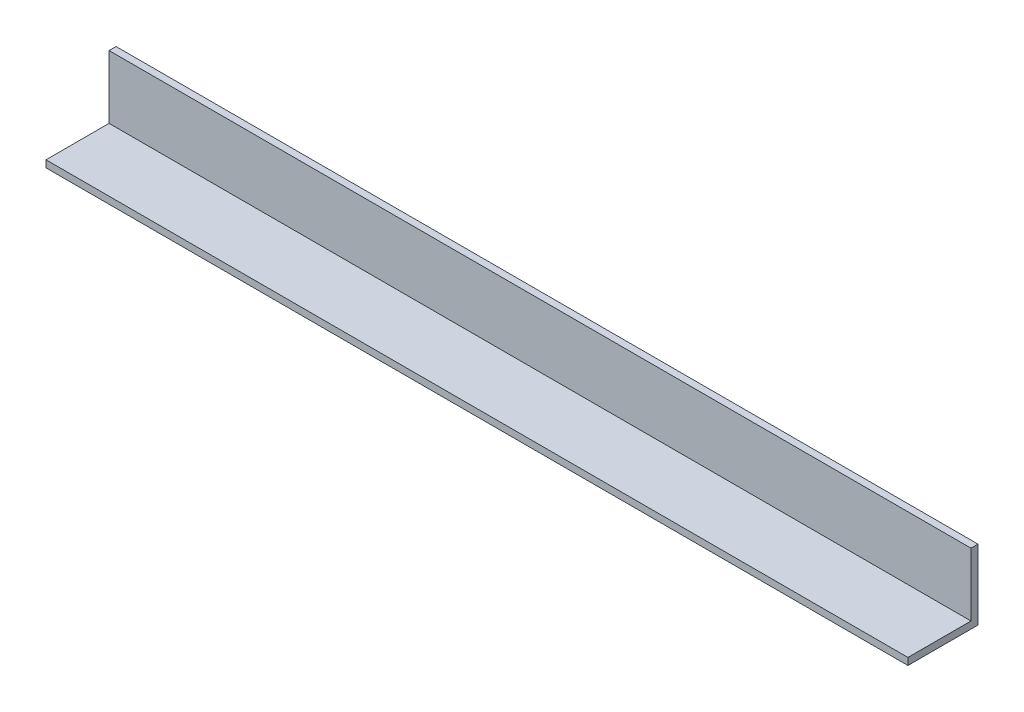
SolidWorks part; units mm, degrees
ref_plane "Front Plane" through (0, 0, 0) normal (0, 0, 1) x (1, 0, 0)
ref_plane "Top Plane" through (0, 0, 0) normal (0, 1, 0) x (1, 0, 0)
ref_plane "Right Plane" through (0, 0, 0) normal (1, 0, 0) x (0, 0, -1)
sketch "Sketch1" plane through (0, 0, 0) normal (1, 0, 0) x (0, 0, -1)
  line L0 (0, 20) -> (0, 0)
  line L1 (0, 0) -> (-20, 0)
  line L2 (-20, 0) -> (-20, 2)
  line L3 (-20, 2) -> (-2, 2)
  line L4 (-2, 2) -> (-2, 20)
  line L5 (-2, 20) -> (0, 20)
  dimension "D1" = 20
  dimension "D2" = 20
  dimension "D3" = 2
  dimension "D4" = 2
extrude "Boss-Extrude1" add sketch "Sketch1" along normal blind 246
